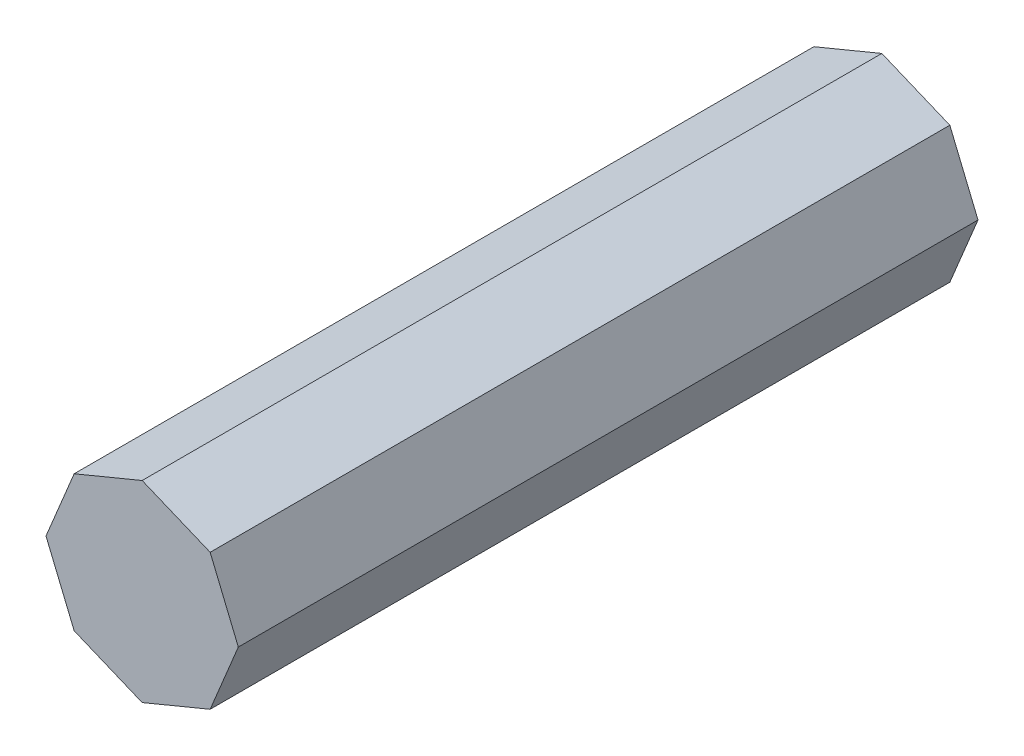
SolidWorks part; units mm, degrees
ref_plane "Front Plane" through (0, 0, 0) normal (0, 0, 1) x (1, 0, 0)
ref_plane "Top Plane" through (0, 0, 0) normal (0, 1, 0) x (1, 0, 0)
ref_plane "Right Plane" through (0, 0, 0) normal (1, 0, 0) x (0, 0, -1)
sketch "Sketch2" plane through (0, 0, 0) normal (0, 0, 1) x (1, 0, 0)
  line L1 (7.8, 0) -> (5.5154, 5.5154)
  line L2 (5.5154, 5.5154) -> (0, 7.8)
  line L3 (0, 7.8) -> (-5.5154, 5.5154)
  line L4 (-5.5154, 5.5154) -> (-7.8, 0)
  line L5 (-7.8, 0) -> (-5.5154, -5.5154)
  line L6 (-5.5154, -5.5154) -> (0, -7.8)
  line L7 (0, -7.8) -> (5.5154, -5.5154)
  line L8 (5.5154, -5.5154) -> (7.8, 0)
  circle A0 centre (0, 0) radius 7.2063 construction
  point P1 (0, 0)
  dimension "D1" = 7.8
extrude "Boss-Extrude1" add sketch "Sketch2" along normal blind 60
sketch "Sketch3" plane through (0, 0, 60) normal (0, 0, 1) x (1, 0, 0)
  line L0 (0, -7.8) -> (5.5154, -5.5154) construction
  line L1 (5.5154, -5.5154) -> (7.8, 0) construction
  arc A0 (-5.5154, 5.5154) -> (0, 7.8) centre (-3.9, 9.4154) ccw
  arc A1 (0, 7.8) -> (5.5154, 5.5154) centre (3.9, 9.4154) ccw
  arc A2 (5.5154, 5.5154) -> (7.8, 0) centre (9.4154, 3.9) ccw
  arc A3 (7.8, 0) -> (5.5154, -5.5154) centre (9.4154, -3.9) ccw
  arc A4 (5.5154, -5.5154) -> (0, -7.8) centre (3.9, -9.4154) ccw
  arc A5 (0, -7.8) -> (-5.5154, -5.5154) centre (-3.9, -9.4154) ccw
  arc A6 (-5.5154, -5.5154) -> (-7.8, 0) centre (-7.9707, -3.3016) ccw
  arc A7 (-7.8, 0) -> (-5.5154, 5.5154) centre (-9.4154, 3.9) ccw
extrude "Boss-Extrude2" add sketch "Sketch3" along normal blind 60
sketch "Sketch4" plane through (-6.6577, -2.7577, 0) normal (-0.9239, -0.3827, 0) x (0, 0, 1)
  line L1 (60, 7.2063) -> (120, 7.2063)
  line L2 (60, 7.2063) -> (60, -7.2063)
  line L3 (60, -7.2063) -> (120, -7.2063)
  line L4 (120, 7.2063) -> (120, -7.2063)
extrude "Cut-Extrude1" cut sketch "Sketch4" against normal blind 60
